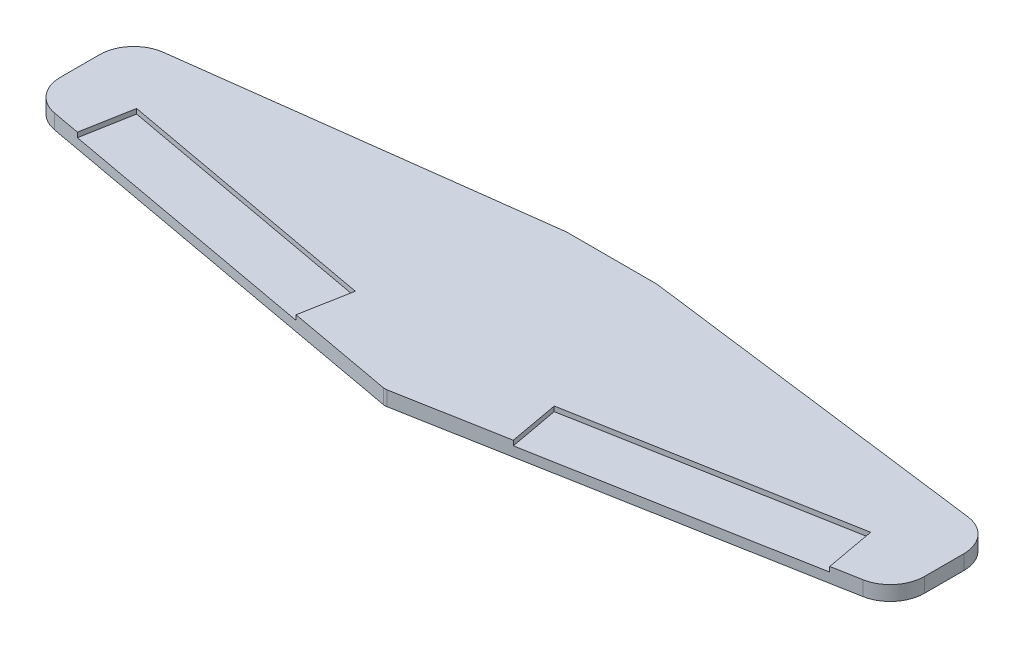
SolidWorks part; units mm, degrees
material "Polyurethane Foam Rigid"
ref_plane "Front Plane" through (0, 0, 0) normal (0, 0, 1) x (1, 0, 0)
ref_plane "Top Plane" through (0, 0, 0) normal (0, 1, 0) x (1, 0, 0)
ref_plane "Right Plane" through (0, 0, 0) normal (1, 0, 0) x (0, 0, -1)
sketch "Sketch1" plane through (0, 0, 0) normal (0, 1, 0) x (1, 0, 0)
  line L0 (0, 21.4991) -> (0, -28.5009) construction
  line L1 (9.2612, 19.1354) -> (-9.2612, 19.1354)
  line L2 (-9.2612, 19.1354) -> (-82.3942, 9.716)
  line L3 (-88.5, 21.4991) -> (88.5, 21.4991) construction
  line L4 (-88.5, -28.5009) -> (88.5, -28.5009) construction
  line L5 (-88.5, 2.7733) -> (-88.5, -5.3011)
  line L6 (-82.7581, -12.1871) -> (0, -27.3068)
  line L7 (82.7581, -12.1871) -> (0, -27.3068)
  line L8 (88.5, 2.7733) -> (88.5, -5.3011)
  line L9 (9.2612, 19.1354) -> (82.3942, 9.716)
  arc A0 (-82.3942, 9.716) -> (-88.5, 2.7733) centre (-81.5, 2.7733) ccw
  arc A1 (-88.5, -5.3011) -> (-82.7581, -12.1871) centre (-81.5, -5.3011) ccw
  arc A2 (88.5, -5.3011) -> (82.7581, -12.1871) centre (81.5, -5.3011) cw
  arc A3 (82.3942, 9.716) -> (88.5, 2.7733) centre (81.5, 2.7733) cw
  point P23 (0, 19.1354)
  dimension "D4" = 7
  dimension "D1" = 50
  dimension "D2" = 88.5
  dimension "D3" = 88.5
extrude "Boss-Extrude1" add sketch "Sketch1" along normal blind 3
fillet "Fillet2" radius 2 1 edges at (0, 1.5, 27.3068)
sketch "Sketch2" plane through (0, 3, 0) normal (0, 1, 0) x (1, 0, 0)
  line L0 (-77.0319, -13.2333) -> (-75.159, -2.982)
  line L1 (-82.7581, -12.1871) -> (-0.3594, -27.2411) construction
  line L2 (-75.159, -2.982) -> (-20.369, -12.992)
  line L3 (-20.369, -12.992) -> (-22.2418, -23.2433)
  line L4 (-22.2418, -23.2433) -> (-77.0319, -13.2333)
  line L5 (0, -55) -> (0, 55) construction
  line L6 (20.369, -12.992) -> (22.2418, -23.2433)
  line L7 (75.159, -2.982) -> (20.369, -12.992)
  line L8 (77.0319, -13.2333) -> (75.159, -2.982)
  line L9 (22.2418, -23.2433) -> (77.0319, -13.2333)
extrude "Cut-Extrude1" cut sketch "Sketch2" against normal blind 1
